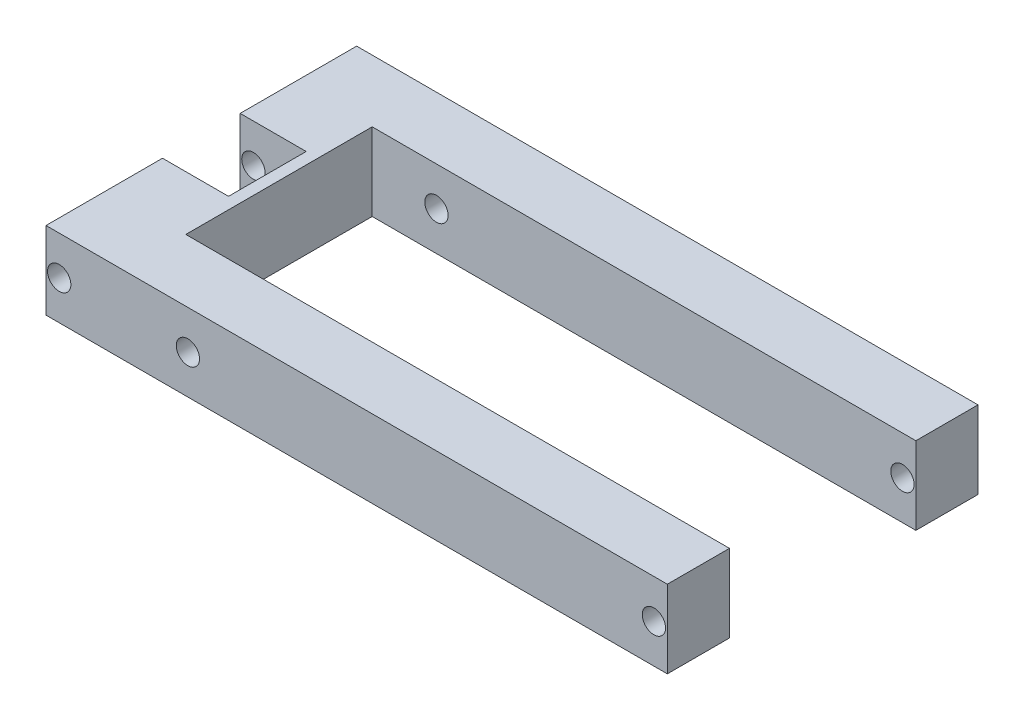
SolidWorks part; units mm, degrees
ref_plane "Piano frontale" through (0, 0, 0) normal (0, 0, 1) x (1, 0, 0)
ref_plane "Piano superiore" through (0, 0, 0) normal (0, 1, 0) x (1, 0, 0)
ref_plane "Piano destro" through (0, 0, 0) normal (1, 0, 0) x (0, 0, -1)
sketch "Schizzo1" plane through (0, 0, 0) normal (0, 1, 0) x (1, 0, 0)
  line L0 (0, 0) -> (-410.3417, 0) construction
  line L1 (0, 0) -> (510.4978, 0) construction
  line L5 (-332.8468, -200) -> (-332.8468, 200)
  line L7 (-332.8468, 200) -> (467.1532, 200)
  line L8 (467.1532, 200) -> (467.1532, 120)
  line L9 (467.1532, 120) -> (-232.8468, 120)
  line L10 (-232.8468, 120) -> (-232.8468, -120)
  line L11 (467.1532, -120) -> (-232.8468, -120)
  line L12 (467.1532, -200) -> (467.1532, -120)
  line L13 (-332.8468, -200) -> (467.1532, -200)
  point P11 (-232.8468, 0)
  point P14 (-332.8468, 0)
  dimension "D1" = 800
  dimension "D2" = 100
  dimension "D4" = 232.8468
  dimension "D3" = 80
  dimension "D5" = 120
extrude "Estrusione-Estrusione1" add sketch "Schizzo1" along normal blind 100
sketch "Schizzo2" plane through (0, 0, 0) normal (0, 0, 1) x (1, 0, 0)
  line L0 (-332.8468, 50) -> (467.1532, 50) construction
  line L8 (-332.8468, 100) -> (-332.8468, 0) construction
  line L13 (467.1532, 100) -> (467.1532, 0) construction
  circle A7 centre (-315.8468, 50) radius 15
  circle A8 centre (-150.1468, 50) radius 15
  circle A9 centre (449.8532, 50) radius 15
  dimension "D1" = 30
  dimension "D2" = 30
  dimension "D3" = 30
  dimension "D4" = 165.7
  dimension "D5" = 600
  dimension "D6" = 17
extrude "Taglio-Estrusione5" cut sketch "Schizzo2" against normal through all both and the other way through all
sketch "Schizzo3" plane through (0, 0, 0) normal (0, 1, 0) x (1, 0, 0)
  line L0 (-14.9222, 0) -> (-32.6568, 0) construction
  line L1 (-332.8468, -50) -> (-332.8468, 50)
  line L2 (-332.8468, 50) -> (-247.8468, 50)
  line L3 (-247.8468, 50) -> (-247.8468, -50)
  line L4 (467.1532, -120) -> (-232.8468, -120)
  line L5 (467.1532, -120) -> (-232.8468, -120)
  line L6 (-232.8468, -120) -> (-232.8468, 120)
  line L7 (-232.8468, -120) -> (-232.8468, 120)
  line L13 (-332.8468, -50) -> (-247.8468, -50)
  line L21 (-232.8468, 120) -> (467.1532, 120)
  line L22 (-232.8468, 120) -> (467.1532, 120)
  line L23 (467.1532, 120) -> (467.1532, 200)
  line L24 (467.1532, 120) -> (467.1532, 200)
  line L25 (467.1532, 200) -> (-332.8468, 200)
  line L26 (467.1532, 200) -> (-332.8468, 200)
  line L27 (-332.8468, 200) -> (-332.8468, -200)
  line L28 (-332.8468, 200) -> (-332.8468, -200)
  line L29 (-332.8468, -200) -> (467.1532, -200)
  line L30 (-332.8468, -200) -> (467.1532, -200)
  line L31 (467.1532, -200) -> (467.1532, -120)
  line L32 (467.1532, -200) -> (467.1532, -120)
  point P21 (-247.8468, 0)
  point P22 (-332.8468, 0)
  dimension "D2" = 85
  dimension "D3" = 0
  dimension "D4" = 50
  dimension "D1" = 0
extrude "Taglio-Estrusione6" cut sketch "Schizzo3" along normal through all both contours L3 L13 L1 L2
